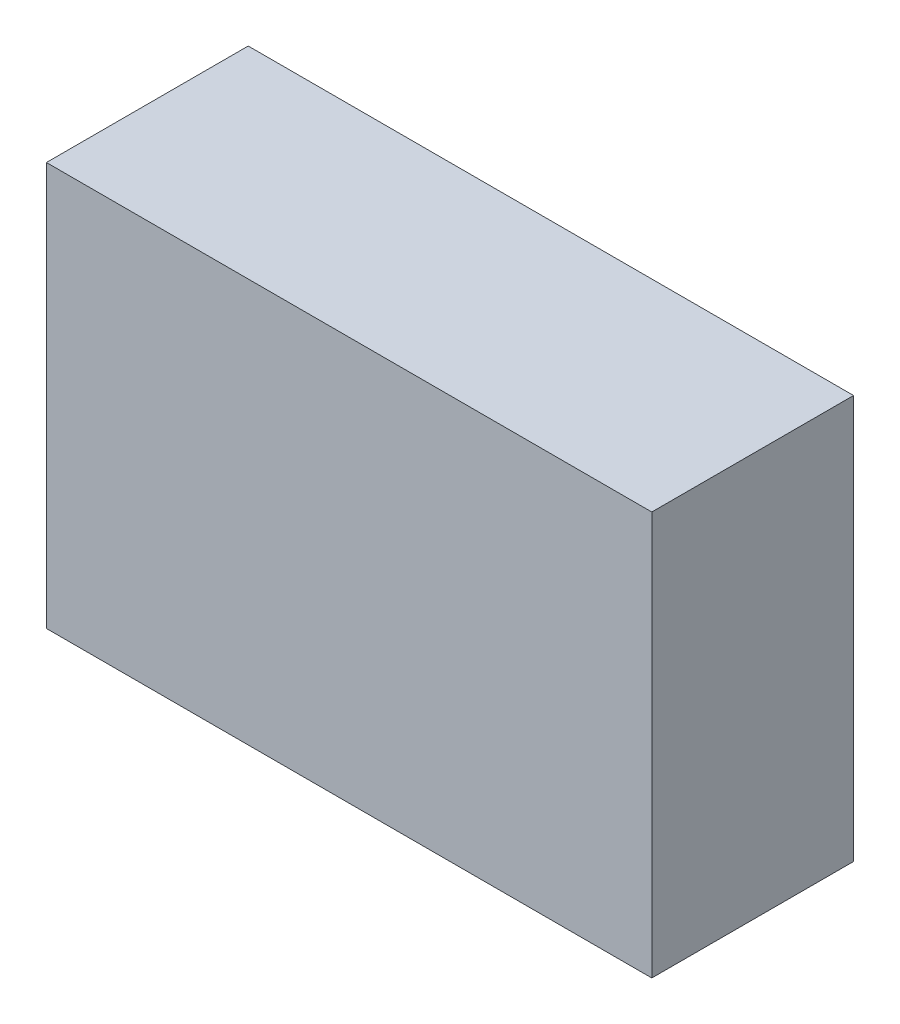
SolidWorks part; units mm, degrees
ref_plane "Alzado" through (0, 0, 0) normal (0, 0, 1) x (1, 0, 0)
ref_plane "Planta" through (0, 0, 0) normal (0, 1, 0) x (1, 0, 0)
ref_plane "Vista lateral" through (0, 0, 0) normal (1, 0, 0) x (0, 0, -1)
sketch "Croquis1" plane through (0, 0, 0) normal (0, 0, 1) x (1, 0, 0)
  line L1 (0.75, -0.5) -> (-0.75, -0.5)
  line L2 (0.75, -0.5) -> (0.75, 0.5)
  line L3 (0.75, 0.5) -> (-0.75, 0.5)
  line L4 (-0.75, -0.5) -> (-0.75, 0.5)
  line L5 (0.75, -0.5) -> (-0.75, 0.5) construction
  line L6 (0.75, 0.5) -> (-0.75, -0.5) construction
  point P0 (0, 0)
  dimension "D1" = 1
  dimension "D2" = 1.5
extrude "Saliente-Extruir1" add sketch "Croquis1" along normal blind 0.5
